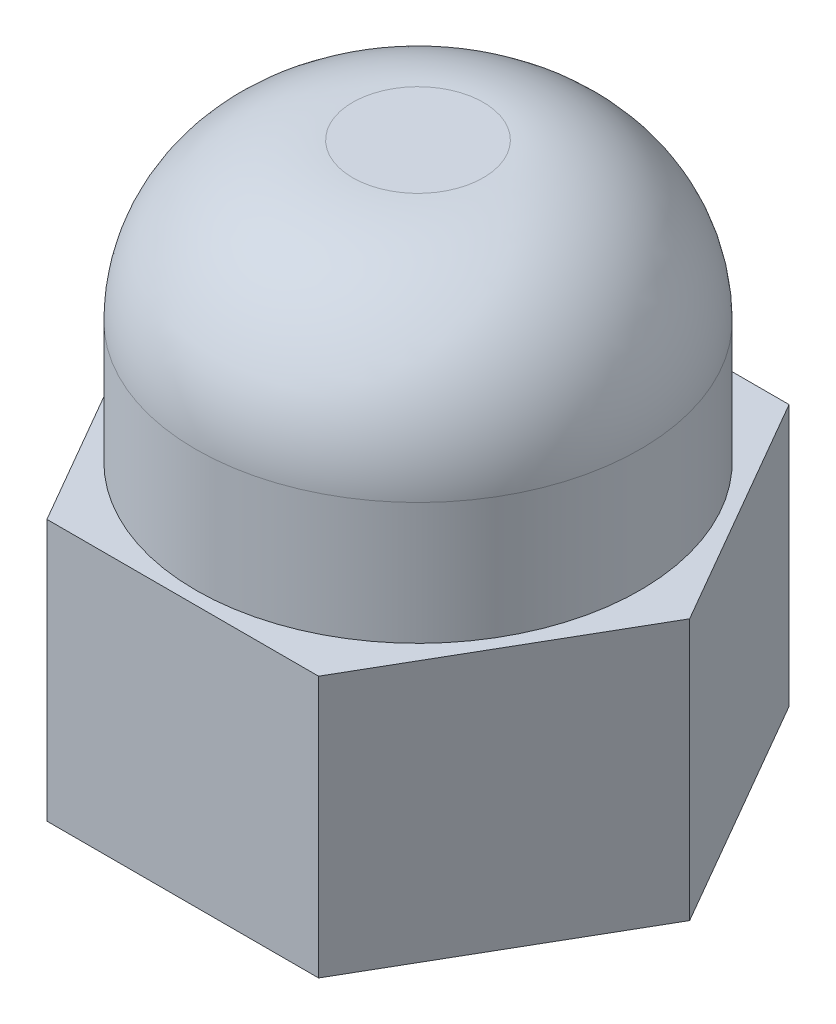
SolidWorks part; units mm, degrees
ref_plane "Plan de face" through (0, 0, 0) normal (0, 0, 1) x (1, 0, 0)
ref_plane "Plan de dessus" through (0, 0, 0) normal (0, 1, 0) x (1, 0, 0)
ref_plane "Plan de droite" through (0, 0, 0) normal (1, 0, 0) x (0, 0, -1)
sketch "Esquisse1" plane through (0, 0, 0) normal (0, 1, 0) x (1, 0, 0)
  line L1 (3.1177, 0) -> (1.5588, 2.7)
  line L2 (1.5588, 2.7) -> (-1.5588, 2.7)
  line L3 (-1.5588, 2.7) -> (-3.1177, 0)
  line L4 (-3.1177, 0) -> (-1.5588, -2.7)
  line L5 (-1.5588, -2.7) -> (1.5588, -2.7)
  line L6 (1.5588, -2.7) -> (3.1177, 0)
  circle A0 centre (0, 0) radius 2.7 construction
  dimension "D1" = 5.4
extrude "Boss.-Extru.1" add sketch "Esquisse1" along normal blind 3
sketch "Esquisse2" plane through (0, 3, 0) normal (0, 1, 0) x (1, 0, 0)
  circle A0 centre (0, 0) radius 2.55
  dimension "D1" = 5.1
extrude "Boss.-Extru.2" add sketch "Esquisse2" along normal blind 3.2
fillet "Congé1" radius 1.8 1 edges at (0, 6.2, 2.55)
hole_wizard "Dégagement M31" positions "Esquisse3" profile "Esquisse5" hole size "M3" standard "ISO"
sketch "Esquisse3" plane through (0, 0, 0) normal (0, -1, 0) x (-1, 0, 0)
  point P0 (0, 0)
sketch "Esquisse5" plane through (0, 0, 0) normal (1, 0, 0) x (0, 0, -1)
  line L0 (0, 0) -> (0, 6.0215)
  line L1 (0, 6.0215) -> (1.7, 5)
  line L2 (1.7, 5) -> (1.7, 0)
  line L5 (1.7, 0) -> (0, 0)
  line L10 (0, 6.0215) -> (-1.7, 5) construction
  line L11 (0, -6.35) -> (0, 107.95) construction
  dimension "Diamètre du perçage" = 3.4
  dimension "Profondeur du perçage" = 5
  dimension "Angle de pointe" = 118
